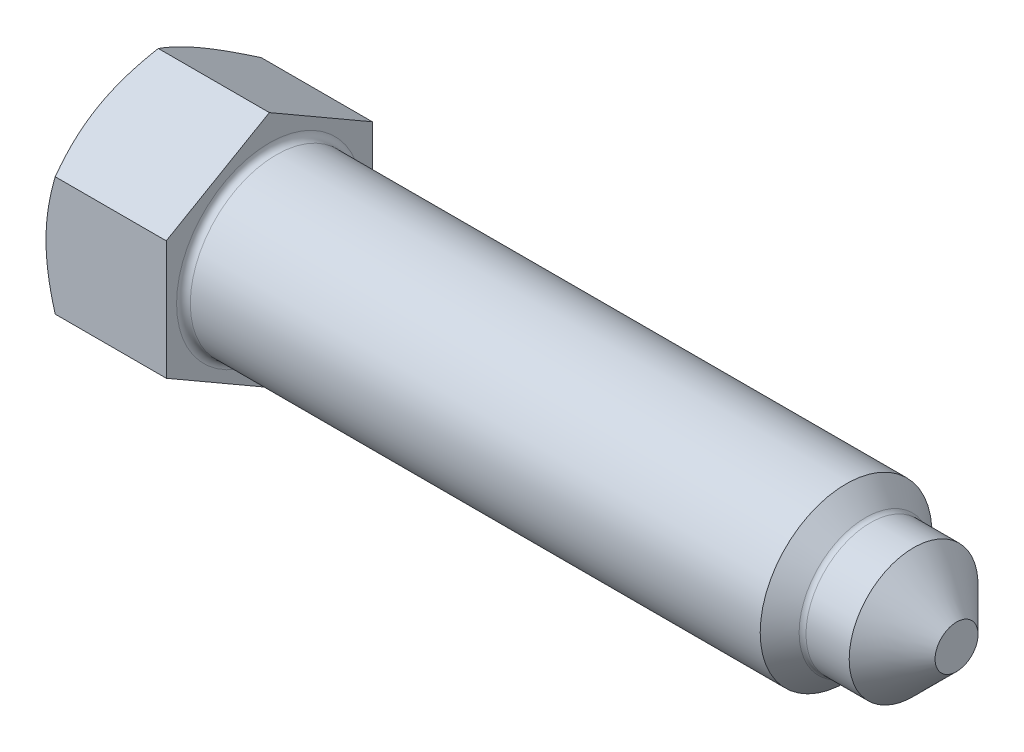
SolidWorks part; units mm, degrees
extrude "BaseHead" add sketch "HexSke" along normal blind 14
sketch "HexSke" plane through (0, 0, 0) normal (1, 0, 0) x (0, 0, -1)
  line L0 (12, 6.9282) -> (12, -6.9282)
  line L1 (-12, 6.9282) -> (-12, -6.9282)
  line L2 (12, -6.9282) -> (0, -13.8564)
  line L3 (0, -13.8564) -> (-12, -6.9282)
  line L4 (12, 6.9282) -> (0, 13.8564)
  line L5 (0, 13.8564) -> (-12, 6.9282)
  dimension "Width_flats" = 24
  dimension "D2" = 120
  dimension "D3" = 12
  dimension "D4" = 12
  dimension "D5" = 12
ref_plane "Plane1" through (0, 0, 0) normal (0, 0, 1) x (1, 0, 0)
ref_plane "Plane2" through (0, 0, 0) normal (0, 1, 0) x (1, 0, 0)
ref_plane "Plane3" through (0, 0, 0) normal (1, 0, 0) x (0, 0, -1)
sketch "BodySke" plane through (0, 0, 0) normal (0, 0, 1) x (1, 0, 0)
  line L0 (0, 6.9282) -> (0, -6.9282) construction
  line L1 (0, 0) -> (94, 0)
  line L2 (0, 0) -> (0, 10)
  line L3 (0, 10) -> (81.14, 10)
  line L4 (94, 0) -> (94, 2.5)
  line L5 (14, 13.8564) -> (14, 6.9282) construction
  line L6 (83.64, 7.5) -> (81.14, 10)
  line L7 (0, 0) -> (105.7297, 0) construction
  line L8 (40.0661, 17) -> (115.5134, 17) construction
  line L9 (0, -10) -> (81.14, -10) construction
  line L10 (16.5, 15.24) -> (16.5, -1.27) construction
  line L11 (89, 7.5) -> (83.64, 7.5)
  line L12 (14, 6.9282) -> (14, -6.9282) construction
  line L13 (89, 7.5) -> (94, 2.5)
  dimension "Body_ch_ang" = 45
  dimension "Minor_dia" = 17
  dimension "Diameter" = 20
revolve "BaseBody" add sketch "BodySke" angle 360 about L7
cosmetic thread "ThreadCosmetic" [suppressed] parameters "Thread_length"=67.14, "Thread_minor"=17
sketch "Sketch3" plane through (0, 0, 0) normal (0, 0, 1) x (1, 0, 0)
  line L0 (0, 12) -> (3.9585, 18.8564)
  line L1 (0, 13.8564) -> (0, 6.9282) construction
  line L2 (3.9585, 18.8564) -> (3.9585, 23.8564)
  line L3 (3.9585, 23.8564) -> (-10, 23.8564)
  line L4 (-10, 23.8564) -> (-10, 12)
  line L5 (-10, 12) -> (0, 12)
  line L6 (0, 0) -> (99.06, 0) construction
  line L7 (14, 13.8564) -> (0, 13.8564) construction
  dimension "D1" = 12
  dimension "D2" = 5
  dimension "D3" = 10
  dimension "D4" = 5
  dimension "Head_ch_ang" = 30
revolve "HeadChamfer" cut sketch "Sketch3" angle 360 about L6
fillet "HeadFillet" radius 0.8 1 edges at (14, 0, -10)
fillet "PointFillet" radius 0.8 1 edges at (83.64, 0, 7.5)
sketch "ThdSchSke" plane through (0, 0, 0) normal (0, 0, 1) x (1, 0, 0)
  line L0 (16.16, -8.5) -> (15.1097, -10)
  line L1 (16.16, -8.5) -> (17.2103, -10)
  line L2 (17.2103, -10) -> (17.2103, -12.5)
  line L3 (-3.175, 0) -> (5.1513, 0) construction
  line L5 (17.2103, -12.5) -> (15.1097, -12.5)
  line L6 (15.1097, -12.5) -> (15.1097, -10)
  dimension "Thread_minor" = 17
  dimension "Diameter" = 20
  dimension "Start" = 16.16
revolve "ThreadSchematic" [suppressed] cut sketch "ThdSchSke" angle 360 about L3
pattern_linear "ThdSchPat" [suppressed]
equation "\"D3@HexSke\" = \"Width_flats@HexSke\" / 2"
equation "\"D4@HexSke\" = \"D3@HexSke\""
equation "\"D5@HexSke\" = \"D4@HexSke\""
equation "\"Thread_minor@ThreadCosmetic\" = \"Minor_dia@BodySke\""
equation "\"D1@Sketch3\" = \"Width_flats@HexSke\" / 2"
equation "\"Thread_length@ThreadCosmetic\" = \"Length@BodySke\" - \"Dog_Lg@BodySke\" - \"Advance@BodySke\""
equation "\"Thread_minor@ThdSchSke\" = \"Minor_dia@BodySke\""
equation "\"Diameter@ThdSchSke\" = \"Diameter@BodySke\""
equation "\"Overcut@ThdSchSke\" = \"Diameter@BodySke\" * 1.25"
equation "\"Start@ThdSchSke\" = \"Fillet_radius@HeadFillet\" + \"Advance@BodySke\" + \"Length@BodySke\" - \"Thread_length@ThreadCosmetic\""
equation "\"Num_threads@ThdSchPat\" = int( \"Thread_length@ThreadCosmetic\" / \"Advance@BodySke\" + 0.999 )  + 1"
equation "\"Advance@ThdSchPat\" = \"Thread_length@ThreadCosmetic\" /  (\"Num_threads@ThdSchPat\" - 1) 'relax it"
equation "\"Num_threads@ThdSchPat\" = \"Num_threads@ThdSchPat\" - sgn( \"Num_threads@ThdSchPat\" - 1) '---chamfered tips only---"
equation "\"Fillet_radius@PointFillet\" = \"Fillet_radius@HeadFillet\""
